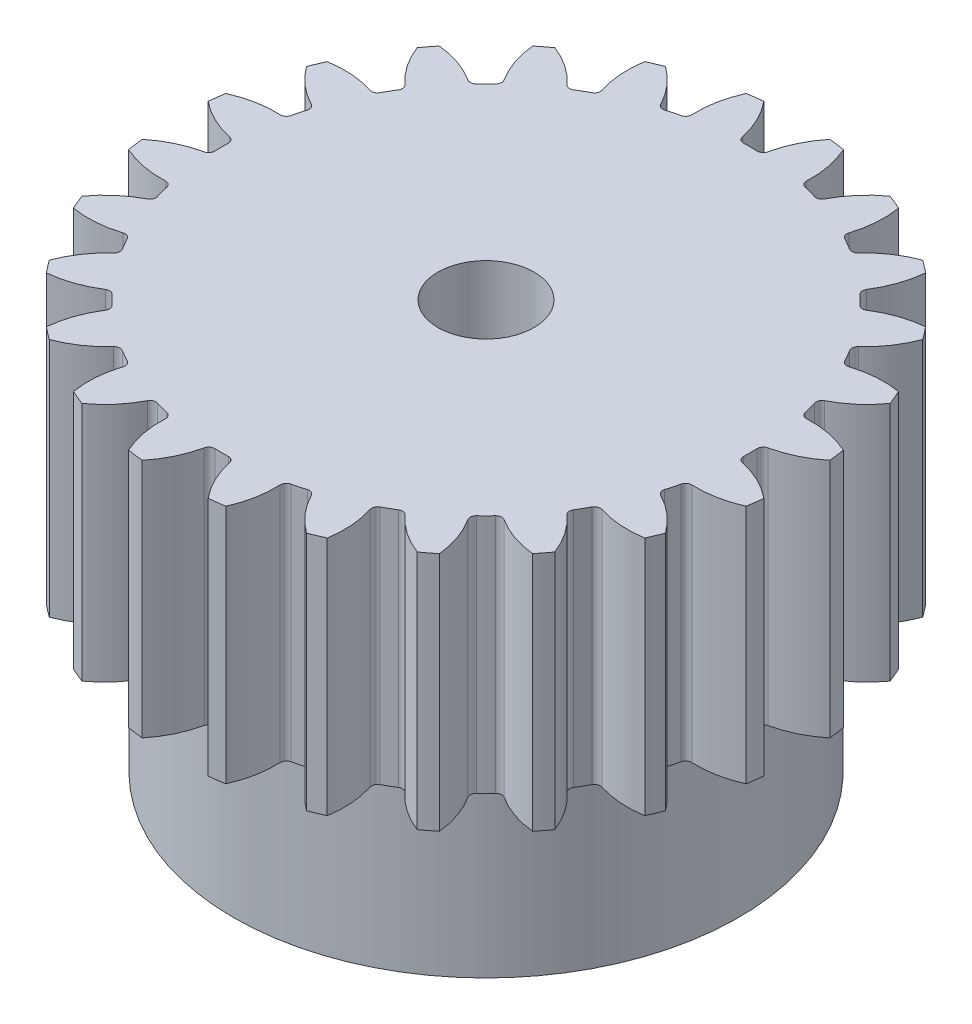
SolidWorks part; units mm, degrees
ref_plane "前视基准面" through (0, 0, 0) normal (0, 0, 1) x (1, 0, 0)
ref_plane "上视基准面" through (0, 0, 0) normal (0, 1, 0) x (1, 0, 0)
ref_plane "右视基准面" through (0, 0, 0) normal (1, 0, 0) x (0, 0, -1)
other "Configuration Table"
sketch "草图1" plane through (0, 0, 0) normal (0, 1, 0) x (1, 0, 0)
  circle A0 centre (0, 0) radius 26
  dimension "D1" = 52
extrude "凸台-拉伸1" add sketch "草图1" along normal blind 20
sketch "草图2" plane through (0, 0, 0) normal (0, 1, 0) x (1, 0, 0)
  circle A0 centre (0, 0) radius 21
  dimension "D1" = 42
extrude "凸台-拉伸2" add sketch "草图2" against normal blind 14
sketch "草图4" plane through (0, 0, 0) normal (0, 1, 0) x (1, 0, 0)
  line L0 (0, 56.0311) -> (0, -31.5538) construction
  line L1 (0, 0) -> (3.6369, 55.4876) construction
  line L2 (1.5697, 23.9486) -> (26.6905, 22.3021) construction
  line L3 (1.5697, 23.9486) -> (25.0859, 13.6012) construction
  line L4 (9.083, 20.6427) -> (0, 0) construction
  circle A0 centre (0, 0) radius 24 construction
  arc A2 (2.7418, 25.855) -> (1.0619, 22.3865) centre (9.083, 20.6427) ccw
  arc A8 (2.7418, 25.855) -> (-2.7418, 25.855) centre (0, 0) ccw
  circle A9 centre (0, 0) radius 26 construction
  arc A15 (0.5605, 21.9929) -> (-0.5605, 21.9929) centre (0, 0) ccw
  arc A16 (1.0619, 22.3865) -> (0.5605, 21.9929) centre (0.5733, 22.4927) cw
  arc A17 (-1.0619, 22.3865) -> (-0.5605, 21.9929) centre (-0.5733, 22.4927) ccw
  arc A18 (-2.7418, 25.855) -> (-1.0619, 22.3865) centre (-9.083, 20.6427) cw
  dimension "D1" = 48
  dimension "D4" = 22
  dimension "D5" = 0.5
  dimension "D2" = 3.75
  dimension "D3" = 20
extrude "切除-拉伸1" cut sketch "草图4" along normal up to next
pattern_circular "阵列(圆周)1" count 24 over 360 about axis through (0, 0, 0) along (0, 1, 0) of "切除-拉伸1"
sketch "草图5" plane through (0, 0, 0) normal (0, 1, 0) x (1, 0, 0)
  circle A0 centre (0, 0) radius 4
  dimension "D1" = 8
extrude "切除-拉伸2" cut sketch "草图5" against normal through all both and the other way through all
sketch "草图6" plane through (0, 0, 0) normal (0, 1, 0) x (1, 0, 0)
  circle A0 centre (0, 0) radius 24 construction
  dimension "D1" = 48
